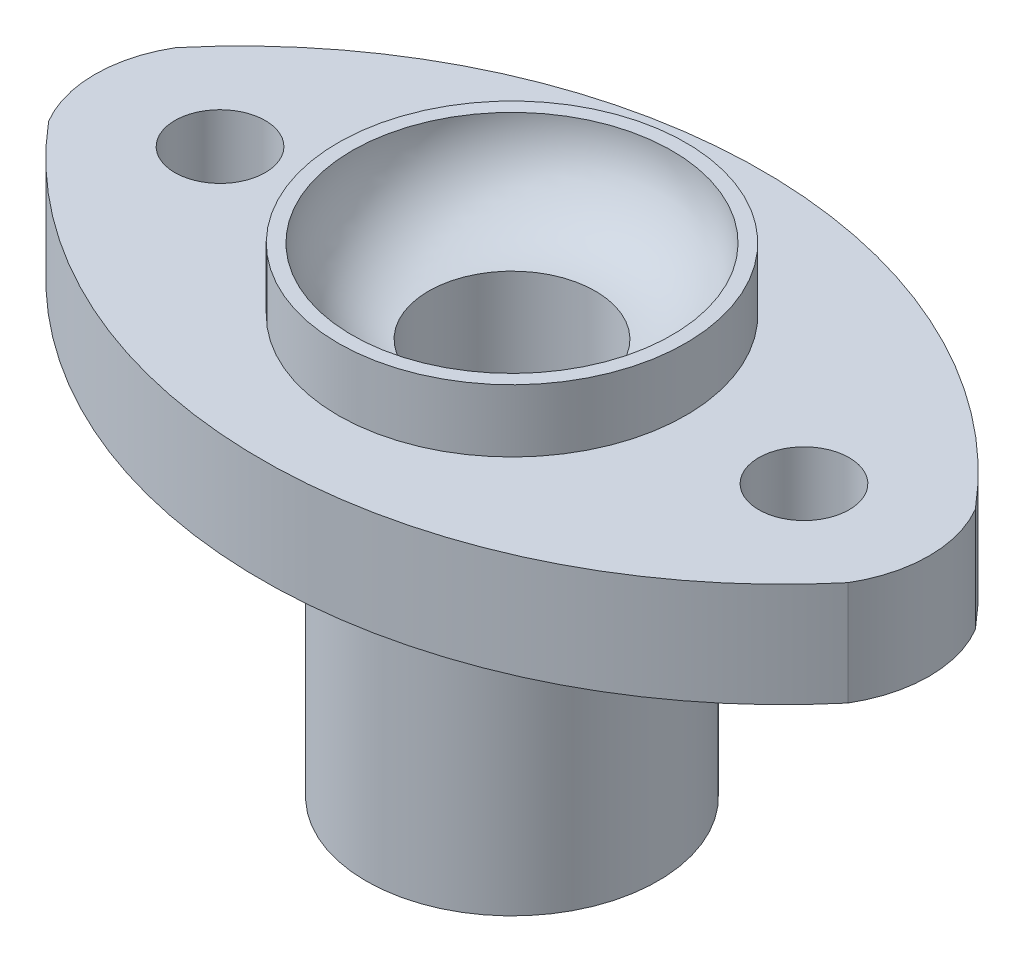
SolidWorks part; units mm, degrees
material "Brass"
ref_plane "Front Plane" through (0, 0, 0) normal (0, 0, 1) x (1, 0, 0)
ref_plane "Top Plane" through (0, 0, 0) normal (0, 1, 0) x (1, 0, 0)
ref_plane "Right Plane" through (0, 0, 0) normal (1, 0, 0) x (0, 0, -1)
sketch "Sketch1" plane through (0, 0, 0) normal (0, 1, 0) x (1, 0, 0)
  circle A0 centre (0, 0) radius 21
  dimension "D1" = 42
extrude "Boss-Extrude1" add sketch "Sketch1" along normal blind 45
sketch "Sketch2" plane through (0, 45, 0) normal (0, 1, 0) x (1, 0, 0)
  line L0 (-60, 0) -> (60, 0) construction
  line L1 (0, -36) -> (0, 36) construction
  circle A0 centre (-42, 0) radius 6.5
  circle A1 centre (42, 0) radius 6.5
  arc A2 (-57.4962, -9.1579) -> (-57.4962, 9.1579) centre (-42, 0) cw
  arc A3 (57.4962, -9.1579) -> (57.4962, 9.1579) centre (42, 0) ccw
  arc A4 (57.4962, 9.1579) -> (-57.4962, 9.1579) centre (0, -39) ccw
  arc A5 (57.4962, -9.1579) -> (-57.4962, -9.1579) centre (0, 39) cw
  point P17 (0, 36)
  point P18 (0, 0)
  point P19 (0, 0)
  point P21 (0, 0)
  dimension "D3" = 13
  dimension "D5" = 18
  dimension "D6" = 75
  dimension "D1" = 120
  dimension "D2" = 72
  dimension "D4" = 84
extrude "Boss-Extrude2" add sketch "Sketch2" along normal blind 15
sketch "Sketch3" plane through (0, 60, 0) normal (0, 1, 0) x (1, 0, 0)
  circle A0 centre (0, 0) radius 25
  dimension "D1" = 50
extrude "Boss-Extrude3" add sketch "Sketch3" along normal blind 9
sketch "Sketch4" plane through (0, 0, 0) normal (0, 0, 1) x (1, 0, 0)
  line L0 (0, 69) -> (0, 57) construction
  line L1 (25, 69) -> (-25, 69) construction
  line L3 (-23, 69) -> (23, 69) construction
  line L4 (-12, 57) -> (12, 57) construction
  line L5 (-12, 57) -> (0, 57)
  line L6 (0, 69) -> (0, 57)
  line L7 (-23, 69) -> (0, 69)
  arc A0 (-23, 69) -> (-12, 57) centre (-11.0001, 68.9583) ccw
  dimension "D4" = 12
  dimension "D1" = 46
  dimension "D2" = 12
  dimension "D3" = 24
revolve "Cut-Revolve1" cut sketch "Sketch4" angle 360 about L6
sketch "Sketch5" plane through (0, 57, 0) normal (0, 1, 0) x (1, 0, 0)
  circle A1 centre (0, 0) radius 12
  circle A2 centre (0, 0) radius 12
  dimension "D1" = 0
extrude "Cut-Extrude1" cut sketch "Sketch5" against normal up to next
chamfer "Chamfer1" distance 2.5 angle 15 1 edges at (0, 0, 12)
